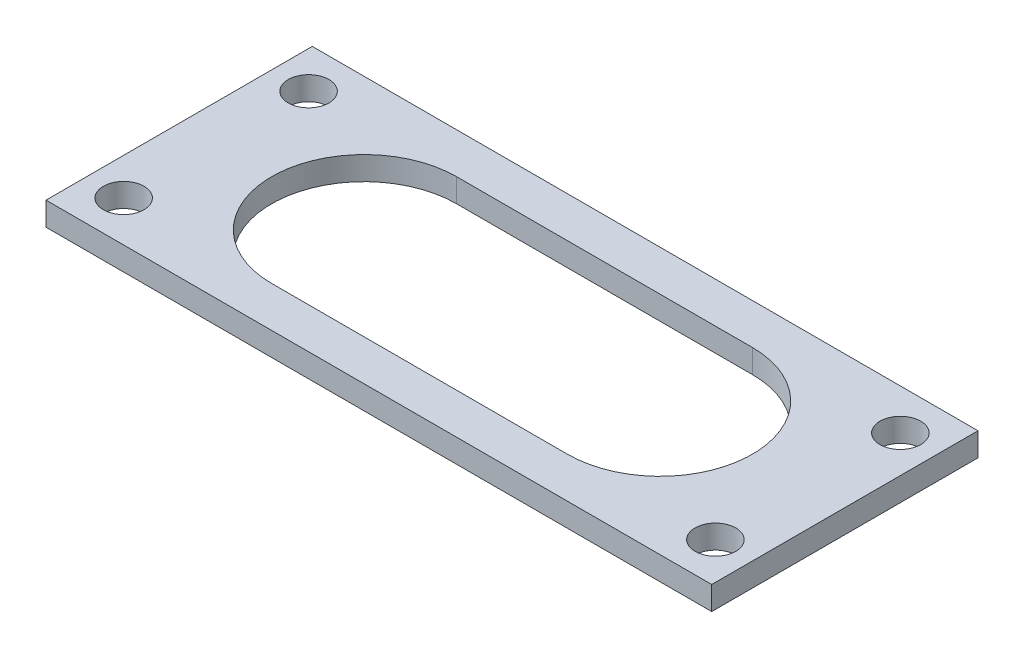
SolidWorks part; units mm, degrees
ref_plane "Front" through (0, 0, 0) normal (0, 0, 1) x (1, 0, 0)
ref_plane "Top" through (0, 0, 0) normal (0, 1, 0) x (1, 0, 0)
ref_plane "Right" through (0, 0, 0) normal (1, 0, 0) x (0, 0, -1)
sketch "Sketch1" plane through (0, 0, 0) normal (0, 1, 0) x (1, 0, 0)
  line L1 (45, -18) -> (-45, -18)
  line L2 (45, -18) -> (45, 18)
  line L3 (45, 18) -> (-45, 18)
  line L4 (-45, -18) -> (-45, 18)
  line L5 (45, -18) -> (-45, 18) construction
  line L6 (45, 18) -> (-45, -18) construction
  point P0 (0, 0)
  dimension "D1" = 90
  dimension "D2" = 36
extrude "Boss-Extrude1" add sketch "Sketch1" along normal blind 3.175
sketch "Sketch2" plane through (0, 3.175, 0) normal (0, 1, 0) x (1, 0, 0)
  line L1 (-40, -12.5) -> (40, -12.5) construction
  line L2 (-40, -12.5) -> (-40, 12.5) construction
  line L3 (-40, 12.5) -> (40, 12.5) construction
  line L4 (40, -12.5) -> (40, 12.5) construction
  line L5 (-40, -12.5) -> (40, 12.5) construction
  line L6 (-40, 12.5) -> (40, -12.5) construction
  circle A0 centre (40, 12.5) radius 2.75
  circle A1 centre (-40, 12.5) radius 2.75
  circle A2 centre (-40, -12.5) radius 2.75
  circle A3 centre (40, -12.5) radius 2.75
  point P0 (0, 0)
  dimension "D1" = 5.5
  dimension "D2" = 80
  dimension "D3" = 25
extrude "Cut-Extrude1" cut sketch "Sketch2" against normal up to next
sketch "Sketch3" plane through (0, 3.175, 0) normal (0, 1, 0) x (1, 0, 0)
  line L0 (20, 0) -> (-20, 0) construction
  line L1 (20, -12.5) -> (-20, -12.5)
  line L2 (20, 12.5) -> (-20, 12.5)
  arc A0 (20, -12.5) -> (20, 12.5) centre (20, 0) ccw
  arc A1 (-20, 12.5) -> (-20, -12.5) centre (-20, 0) ccw
  point P2 (0, 0)
  dimension "D1" = 40
  dimension "D2" = 25
extrude "Cut-Extrude2" cut sketch "Sketch3" against normal up to next
